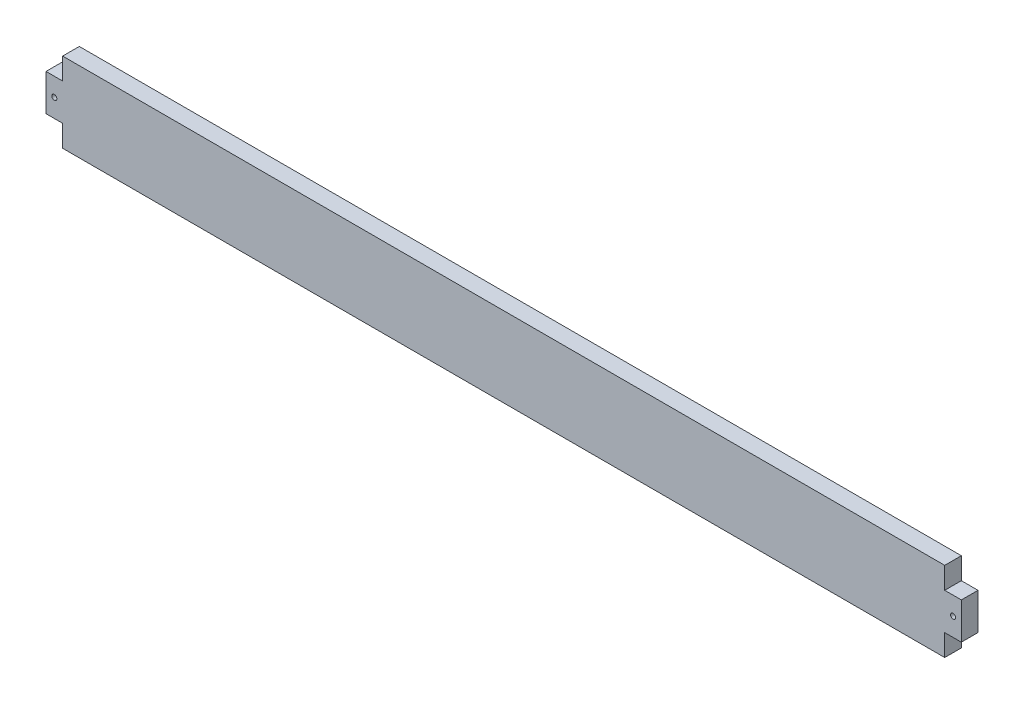
SolidWorks part; units mm, degrees
material "Teak"
ref_plane "Front Plane" through (0, 0, 0) normal (0, 0, 1) x (1, 0, 0)
ref_plane "Top Plane" through (0, 0, 0) normal (0, 1, 0) x (1, 0, 0)
ref_plane "Right Plane" through (0, 0, 0) normal (1, 0, 0) x (0, 0, -1)
sketch "Sketch1" plane through (0, 0, 0) normal (0, 0, 1) x (1, 0, 0)
  line L1 (-275, 24) -> (275, 24)
  line L2 (-275, 24) -> (-275, -24)
  line L3 (-275, -24) -> (275, -24)
  line L4 (275, 24) -> (275, -24)
  line L5 (-275, 24) -> (275, -24) construction
  line L6 (-275, -24) -> (275, 24) construction
  point P0 (0, 0)
  dimension "D1" = 550
  dimension "D2" = 48
extrude "Основа" add sketch "Sketch1" along normal blind 10
sketch "Sketch2" plane through (0, 0, 10) normal (0, 0, 1) x (1, 0, 0)
  line L0 (-275, -11) -> (-265, -11)
  line L1 (-275, 24) -> (-275, -24) construction
  line L2 (-265, -11) -> (-265, 11) construction
  line L3 (-265, 11) -> (-275, 11)
  line L4 (-275, 11) -> (-275, -11) construction
  line L5 (0, 24) -> (0, -24) construction
  line L6 (275, 24) -> (-275, 24) construction
  line L7 (-275, -24) -> (275, -24) construction
  line L8 (-275, -11) -> (-275, -24)
  line L9 (-275, -24) -> (-265, -24)
  line L10 (-265, -24) -> (-265, -11)
  line L11 (-275, 24) -> (-275, 11)
  line L12 (-265, 11) -> (-265, 24)
  line L13 (-265, 24) -> (-275, 24)
  point P13 (-275, 0)
  point P14 (-275, 0)
  dimension "D1" = 10
  dimension "D2" = 22
extrude "Шип" cut sketch "Sketch2" against normal up to next
sketch "Sketch3" plane through (0, 0, 10) normal (0, 0, 1) x (1, 0, 0)
  line L3 (-275, 11) -> (-265, 11) construction
  line L4 (-275, 11) -> (-275, -11) construction
  circle A2 centre (-270, 0) radius 1.5
  point P2 (0, 0)
  point P5 (-270, 11)
  point P6 (0, 0)
  point P9 (-275, 0)
  dimension "D1" = 3
extrude "Крепежные" cut sketch "Sketch3" against normal up to next
mirror "Mirror1" about plane through (0, 0, 0) normal (1, 0, 0) of "Крепежные", "Шип"
